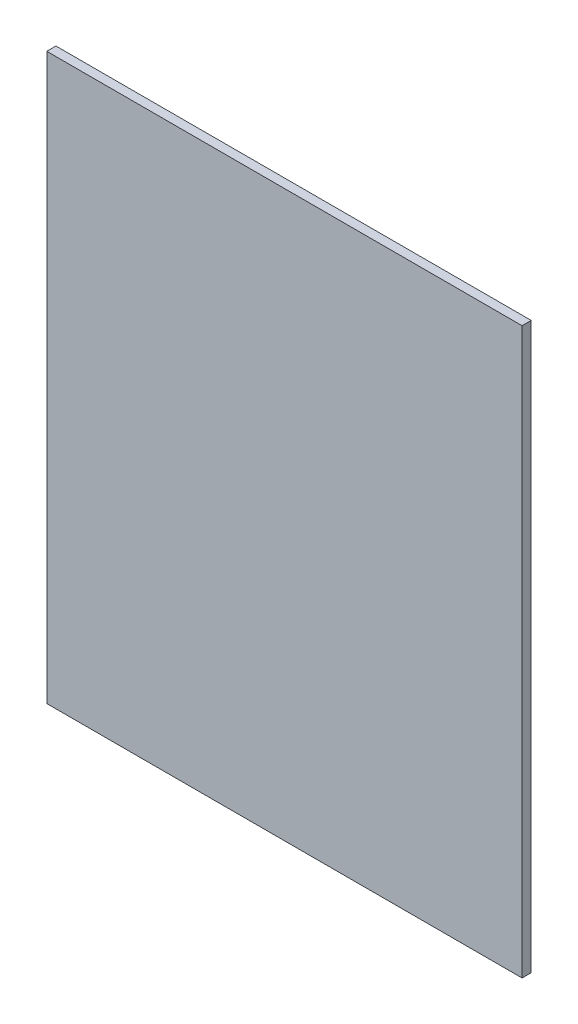
SolidWorks part; units mm, degrees
ref_plane "Plan de face" through (0, 0, 0) normal (0, 0, 1) x (1, 0, 0)
ref_plane "Plan de dessus" through (0, 0, 0) normal (0, 1, 0) x (1, 0, 0)
ref_plane "Plan de droite" through (0, 0, 0) normal (1, 0, 0) x (0, 0, -1)
sketch "Esquisse1" plane through (0, 0, 0) normal (0, 0, 1) x (1, 0, 0)
  line L1 (130, -154.5) -> (-130, -154.5)
  line L2 (130, -154.5) -> (130, 154.5)
  line L3 (130, 154.5) -> (-130, 154.5)
  line L4 (-130, -154.5) -> (-130, 154.5)
  line L5 (130, -154.5) -> (-130, 154.5) construction
  line L6 (130, 154.5) -> (-130, -154.5) construction
  point P0 (0, 0)
  dimension "D1" = 260
  dimension "D2" = 309
extrude "Boss.-Extru.1" add sketch "Esquisse1" along normal blind 5
